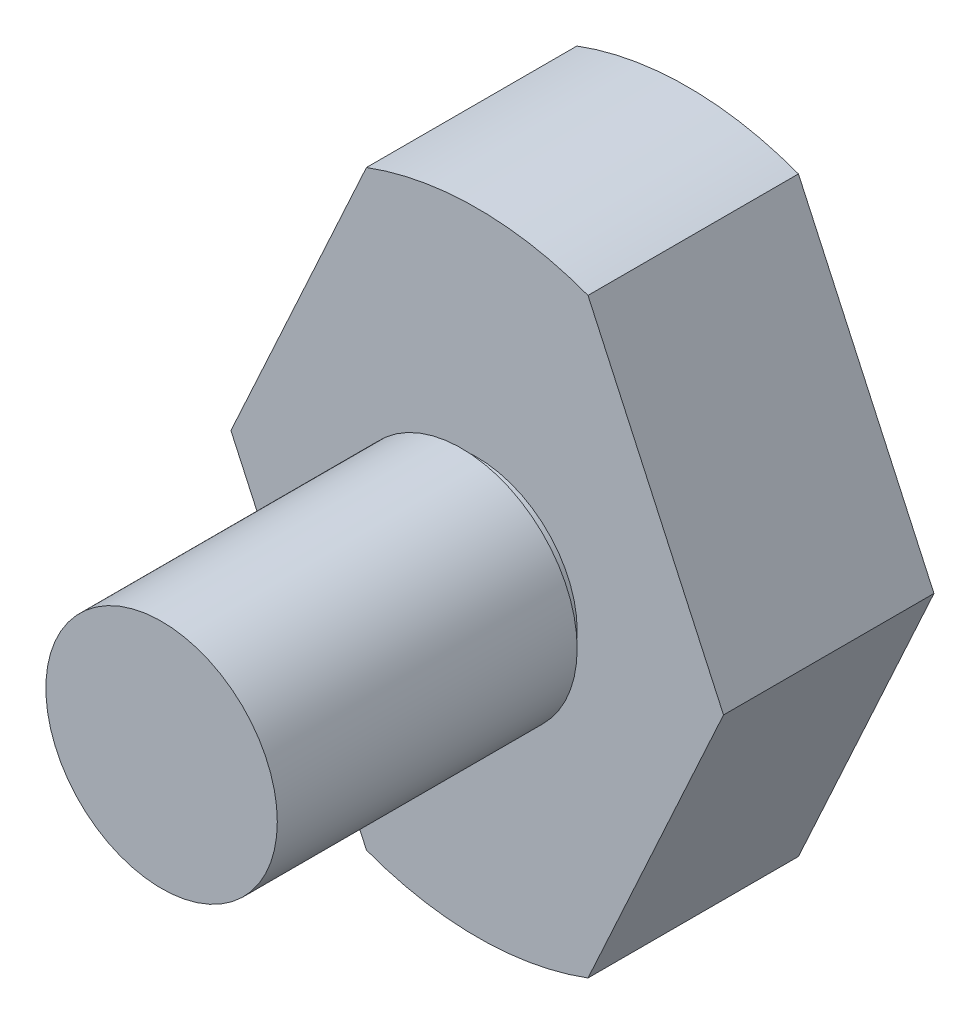
SolidWorks part; units mm, degrees
ref_plane "前视基准面" through (0, 0, 0) normal (0, 0, 1) x (1, 0, 0)
ref_plane "上视基准面" through (0, 0, 0) normal (0, 1, 0) x (1, 0, 0)
ref_plane "右视基准面" through (0, 0, 0) normal (1, 0, 0) x (0, 0, -1)
sketch "草图1" plane through (0, 0, 0) normal (0, 1, 0) x (1, 0, 0)
  line L0 (0, 0) -> (0, 50)
  line L2 (30, 30) -> (30, 50)
  line L3 (30, 30) -> (9.5, 30)
  line L4 (9.5, 30) -> (9.5, 28.5)
  line L5 (9.5, 28.5) -> (11, 28.5)
  line L6 (11, 28.5) -> (11, 0)
  line L7 (11, 0) -> (0, 0)
  line L8 (30, 50) -> (0, 50)
  dimension "D1" = 30
  dimension "D2" = 1.5
  dimension "D3" = 1.5
  dimension "D4" = 11
  dimension "D5" = 20
revolve "旋转1" add sketch "草图1" angle 360 about L0
sketch "草图2" plane through (0, 0, -50) normal (0, 0, -1) x (-1, 0, 0)
  line L3 (-10.5276, 28.0922) -> (-23.4095, 0)
  line L7 (-10.5276, -28.0922) -> (-23.4095, 0)
  line L8 (10.5276, -28.0922) -> (23.4095, 0)
  line L9 (10.5276, 28.0922) -> (23.4095, 0)
  circle A0 centre (0, 0) radius 30 construction
  arc A1 (-10.5276, -28.0922) -> (10.5276, -28.0922) centre (0, 0) ccw
  arc A2 (10.5276, 28.0922) -> (-10.5276, 28.0922) centre (0, 0) ccw
  circle A3 centre (0, 0) radius 36.2393
extrude "切除-拉伸1" cut sketch "草图2" against normal blind 30
